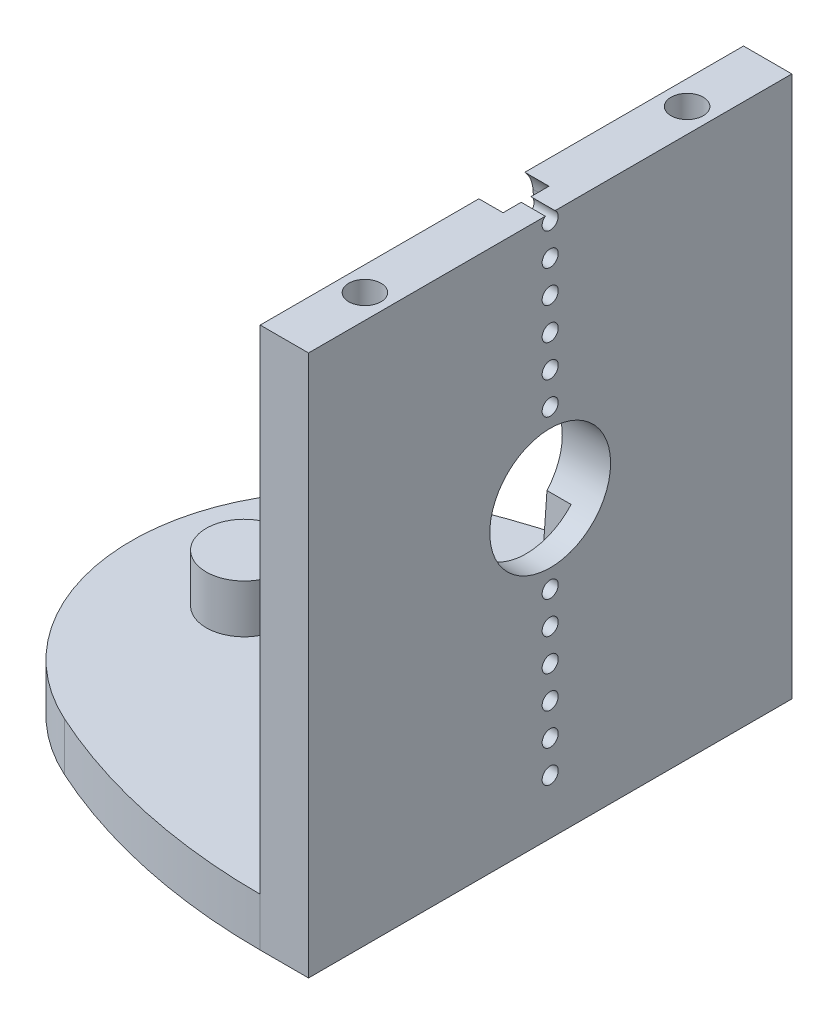
SolidWorks part; units mm, degrees
material "ABS"
ref_plane "Front Plane" through (0, 0, 0) normal (0, 0, 1) x (1, 0, 0)
ref_plane "Top Plane" through (0, 0, 0) normal (0, 1, 0) x (1, 0, 0)
ref_plane "Right Plane" through (0, 0, 0) normal (1, 0, 0) x (0, 0, -1)
sketch "Sketch1" plane through (0, 0, 0) normal (0, 1, 0) x (1, 0, 0)
  line L0 (0, 0) -> (11.2501, 0) construction
  line L1 (0.5, -11.6445) -> (0.5, 11.6445) construction
  line L12 (-7, 15) -> (19, 15)
  line L13 (-7, 15) -> (-7, -15)
  line L14 (-7, -15) -> (19, -15)
  line L15 (19, 15) -> (19, -15)
  line L16 (16, -15) -> (19, -15) construction
  line L17 (19, 15) -> (16, 15)
  line L18 (19, 15) -> (19, -15)
  line L19 (19, -15) -> (16, -15)
  line L20 (16, 15) -> (16, -15)
  line L21 (17.5, -15) -> (17.5, 15) construction
  circle A13 centre (0, 0) radius 2.35 construction
  arc A16 (16, -15) -> (0.5, -11.6445) centre (16, 22.4771) cw
  arc A17 (16, 15) -> (0.5, 11.6445) centre (16, -22.4771) ccw
  arc A18 (0.5, 11.6445) -> (0.5, -11.6445) centre (5.7896, 0) ccw
  dimension "D4" = 30
  dimension "D3" = 17
  dimension "D2" = 4.7
  dimension "D10" = 26
  dimension "D11" = 7
  dimension "D12" = 3
extrude "Boss-Extrude1" add sketch "Sketch1" against normal blind 3
sketch "Esquisse1" plane through (0, 0, 0) normal (0, 1, 0) x (1, 0, 0)
  line L1 (19, 15) -> (16, 15)
  line L2 (19, 15) -> (19, -15)
  line L3 (19, -15) -> (16, -15)
  line L4 (16, 15) -> (16, -15)
extrude "Boss.-Extru.1" add sketch "Esquisse1" along normal blind 30.6
sketch "Esquisse2" plane through (0, 30.6, 0) normal (0, 1, 0) x (1, 0, 0)
  line L0 (17.5, -10) -> (17.5, 10) construction
  line L1 (14.3016, 0) -> (21.3682, 0) construction
  line L2 (16, -15) -> (19, -15) construction
  line L3 (19, 15) -> (16, 15) construction
  line L4 (16, 15) -> (16, -15) construction
  line L5 (19, -15) -> (19, 15) construction
  circle A2 centre (17.5, 10) radius 1
  circle A4 centre (17.5, -10) radius 1
  dimension "D1" = 2
  dimension "D2" = 2
  dimension "D3" = 20
extrude "Enlèv. mat.-Extru.1" cut sketch "Esquisse2" against normal blind 3
sketch "Esquisse3" plane through (0, 0, 0) normal (0, 1, 0) x (1, 0, 0)
  circle A0 centre (0, 0) radius 2.35 construction
  circle A1 centre (0, 0) radius 2.35
extrude "Boss.-Extru.2" add sketch "Esquisse3" along normal blind 3
sketch "Esquisse4" plane through (16, 0, 0) normal (-1, 0, 0) x (0, 0, 1)
  line L0 (-15, 15.3) -> (15, 15.3) construction
  line L1 (-15, 30.6) -> (-15, 0) construction
  line L2 (15, 30.6) -> (15, 0) construction
  line L3 (0, 0) -> (0, 30.6) construction
  line L4 (-15, 0) -> (15, 0) construction
  line L5 (-15, 30.6) -> (15, 30.6) construction
  circle A0 centre (0, 15.3) radius 2.5
  dimension "D1" = 5
extrude "Enlèv. mat.-Extru.2" cut sketch "Esquisse4" against normal through all
sketch "Esquisse5" plane through (16, 0, 0) normal (-1, 0, 0) x (0, 0, 1)
  line L4 (-2.8, 12.8055) -> (-1.9323, 1.1686)
  line L5 (1.9323, 1.1686) -> (2.8, 12.8055)
  line L6 (2.8, 17.7945) -> (1.9323, 29.4314)
  line L7 (-1.9323, 29.4314) -> (-2.8, 17.7945)
  line L8 (-2.8, 12.8055) -> (-1.9323, 1.1686)
  line L9 (1.9323, 1.1686) -> (2.8, 12.8055)
  line L10 (2.8, 17.7945) -> (1.9323, 29.4314)
  line L11 (-1.9323, 29.4314) -> (-2.8, 17.7945)
  arc A2 (2.8, 12.8055) -> (2.8, 17.7945) centre (0, 15.3) ccw
  arc A3 (-2.8, 17.7945) -> (-2.8, 12.8055) centre (0, 15.3) ccw
  arc A4 (2.8, 12.8055) -> (2.8, 17.7945) centre (0, 15.3) ccw
  arc A5 (-2.8, 17.7945) -> (-2.8, 12.8055) centre (0, 15.3) ccw
  spline S2 degree 2 poles (4784.3558, 1444.2062) (-32.2529, 63.9149) (-1.7461, 0.4725) (-1.5874, 0.1427) (-1.3186, -0.1072) (-1.0506, -0.3562) (-0.7092, -0.4906) (-0.3678, -0.6249) (0, -0.625) (0.3662, -0.6251) (0.708, -0.491) (1.0487, -0.3574) (1.3179, -0.1078) (1.5861, 0.1409) (1.7455, 0.4714) (32.2611, 63.7434) (-4772.9463, 1481.2877) knots -23.891246 -23.891246 -23.891246 0.125 0.125 0.25 0.25 0.375 0.375 0.5 0.5 0.625 0.625 0.75 0.75 0.875 0.875 24.829598 24.829598 24.829598 only from (-1.9323, 1.1686) to (1.9323, 1.1686)
  spline S3 degree 2 poles (-4784.3558, -1413.6062) (32.2529, -33.3149) (1.7461, 30.1275) (1.5874, 30.4573) (1.3186, 30.7072) (1.0506, 30.9562) (0.7092, 31.0906) (0.3678, 31.2249) (0, 31.225) (-0.3662, 31.2251) (-0.708, 31.091) (-1.0487, 30.9574) (-1.3179, 30.7078) (-1.5861, 30.4591) (-1.7455, 30.1286) (-32.2611, -33.1434) (4772.9463, -1450.6877) knots -23.891246 -23.891246 -23.891246 0.125 0.125 0.25 0.25 0.375 0.375 0.5 0.5 0.625 0.625 0.75 0.75 0.875 0.875 24.829598 24.829598 24.829598 only from (1.9323, 29.4314) to (-1.9323, 29.4314)
  spline S4 degree 2 poles (-1.9323, 1.1686) (-1.9048, 0.8027) (-1.7461, 0.4725) (-1.5874, 0.1427) (-1.3186, -0.1072) (-1.0506, -0.3562) (-0.7092, -0.4906) (-0.3678, -0.6249) (0, -0.625) (0.3662, -0.6251) (0.708, -0.491) (1.0487, -0.3574) (1.3179, -0.1078) (1.5861, 0.1409) (1.7455, 0.4714) (1.9047, 0.8016) (1.9323, 1.1686) knots 0 0 0 0.125 0.125 0.25 0.25 0.375 0.375 0.5 0.5 0.625 0.625 0.75 0.75 0.875 0.875 1 1 1
  spline S5 degree 2 poles (1.9323, 29.4314) (1.9048, 29.7973) (1.7461, 30.1275) (1.5874, 30.4573) (1.3186, 30.7072) (1.0506, 30.9562) (0.7092, 31.0906) (0.3678, 31.2249) (0, 31.225) (-0.3662, 31.2251) (-0.708, 31.091) (-1.0487, 30.9574) (-1.3179, 30.7078) (-1.5861, 30.4591) (-1.7455, 30.1286) (-1.9047, 29.7984) (-1.9323, 29.4314) knots 0 0 0 0.125 0.125 0.25 0.25 0.375 0.375 0.5 0.5 0.625 0.625 0.75 0.75 0.875 0.875 1 1 1
  dimension "D1" = 0
extrude "Enlèv. mat.-Extru.3" cut sketch "Esquisse5" against normal blind 1.5 and the other way blind 5
sketch "Esquisse6" plane through (19, 0, 0) normal (1, 0, 0) x (0, 0, -1)
  circle A0 centre (0, 30.2) radius 0.5 construction
  circle A1 centre (0, 28.2) radius 0.5 construction
  circle A2 centre (0, 26.2) radius 0.5 construction
  circle A3 centre (0, 24.2) radius 0.5 construction
  circle A4 centre (0, 22.2) radius 0.5 construction
  circle A5 centre (0, 20.2) radius 0.5 construction
  circle A6 centre (0, 10.4) radius 0.5 construction
  circle A7 centre (0, 8.4) radius 0.5 construction
  circle A8 centre (0, 6.4) radius 0.5 construction
  circle A9 centre (0, 4.4) radius 0.5 construction
  circle A10 centre (0, 2.4) radius 0.5 construction
  circle A11 centre (0, 0.4) radius 0.5 construction
  circle A12 centre (0, 30.2) radius 0.5
  circle A13 centre (0, 28.2) radius 0.5
  circle A14 centre (0, 26.2) radius 0.5
  circle A15 centre (0, 24.2) radius 0.5
  circle A16 centre (0, 22.2) radius 0.5
  circle A17 centre (0, 20.2) radius 0.5
  circle A18 centre (0, 10.4) radius 0.5
  circle A19 centre (0, 8.4) radius 0.5
  circle A20 centre (0, 6.4) radius 0.5
  circle A21 centre (0, 4.4) radius 0.5
  circle A22 centre (0, 2.4) radius 0.5
  circle A23 centre (0, 0.4) radius 0.5
  circle A24 centre (0, 15.3) radius 3.75 construction
  circle A25 centre (0, 15.3) radius 3.75
extrude "Enlèv. mat.-Extru.4" cut sketch "Esquisse6" against normal up to surface (3 mm away) up to face at (16, 15.1539, 5.4082)
